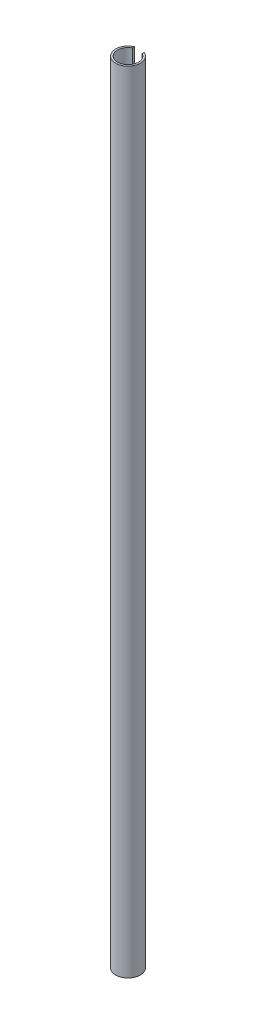
SolidWorks part; units mm, degrees
material "AISI 316 Stainless Steel Sheet (SS)"
ref_plane "Front Plane" through (0, 0, 0) normal (0, 0, 1) x (1, 0, 0)
ref_plane "Top Plane" through (0, 0, 0) normal (0, 1, 0) x (1, 0, 0)
ref_plane "Right Plane" through (0, 0, 0) normal (1, 0, 0) x (0, 0, -1)
sketch "Sketch1" plane through (0, 0, 0) normal (0, 1, 0) x (1, 0, 0)
  circle A0 centre (0, 0) radius 4.7625
  circle A1 centre (0, 0) radius 4.0513
  dimension "D1" = 8.1026
  dimension "D2" = 9.525
extrude "Shaft" add sketch "Sketch1" against normal blind 304.8
sketch "Sketch2" plane through (0, 0, 0) normal (0, 0, 1) x (1, 0, 0)
  line L0 (4.0513, 0) -> (-4.0513, 0) construction
  line L1 (-1.27, -6.35) -> (1.27, -6.35)
  line L2 (-1.905, -5.715) -> (-1.905, 0)
  line L3 (-1.905, 0) -> (1.905, 0)
  line L4 (1.905, -5.715) -> (1.905, 0)
  line L5 (-1.905, -6.35) -> (1.905, 0) construction
  line L6 (-1.905, 0) -> (1.905, -6.35) construction
  arc A0 (-1.27, -6.35) -> (-1.905, -5.715) centre (-1.27, -5.715) cw
  arc A1 (1.27, -6.35) -> (1.905, -5.715) centre (1.27, -5.715) ccw
  point P0 (0, -3.175)
  dimension "D3" = 0.635
  dimension "D1" = 6.35
  dimension "D2" = 3.81
extrude "Cutaway" cut sketch "Sketch2" against normal through all
